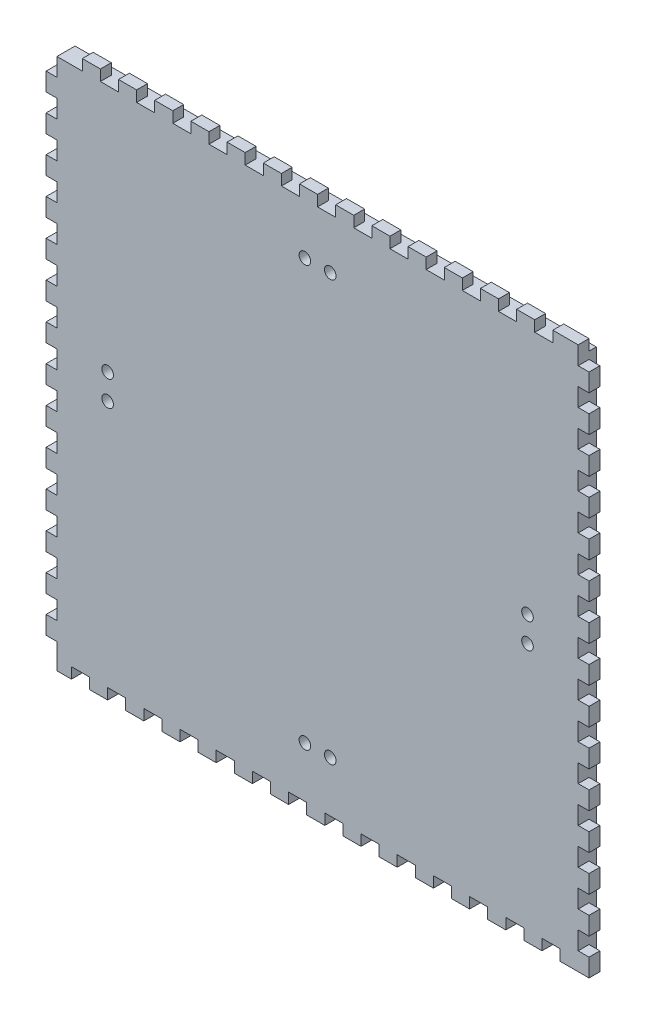
SolidWorks part; units mm, degrees
ref_plane "Front Plane" through (0, 0, 0) normal (0, 0, 1) x (1, 0, 0)
ref_plane "Top Plane" through (0, 0, 0) normal (0, 1, 0) x (1, 0, 0)
ref_plane "Right Plane" through (0, 0, 0) normal (1, 0, 0) x (0, 0, -1)
sketch "Sketch1" plane through (0, 0, 0) normal (0, 0, 1) x (1, 0, 0)
  line L1 (-75, 75) -> (75, 75)
  line L2 (-75, 75) -> (-75, -75)
  line L3 (-75, -75) -> (75, -75)
  line L4 (75, 75) -> (75, -75)
  line L5 (-75, 75) -> (75, -75) construction
  line L6 (-75, -75) -> (75, 75) construction
  point P0 (0, 0)
  dimension "D1" = 150
  dimension "D2" = 150
extrude "Boss-Extrude1" add sketch "Sketch1" along normal blind 5
sketch "Sketch2" plane through (0, 75, 0) normal (0, 1, 0) x (1, 0, 0)
  line L1 (-75, 0) -> (72, 0)
  line L2 (-75, 0) -> (-75, -2)
  line L3 (-75, -2) -> (72, -2)
  line L4 (72, 0) -> (72, -2)
  dimension "D1" = 2
  dimension "D2" = 3
extrude "Cut-Extrude1" cut sketch "Sketch2" against normal blind 3
sketch "Sketch3" plane through (0, 75, 0) normal (0, 1, 0) x (1, 0, 0)
  line L0 (75, -5) -> (-75, -5) construction
  line L1 (-60, -5) -> (-55, -5)
  line L2 (-60, -5) -> (-60, -2)
  line L3 (-60, -2) -> (-55, -2)
  line L4 (-55, -5) -> (-55, -2)
  line L5 (-75, -2) -> (72, -2) construction
  line L6 (-75, -5) -> (-75, -2) construction
  dimension "D1" = 5
  dimension "D2" = 15
extrude "Cut-Extrude2" cut sketch "Sketch3" against normal blind 3
pattern_linear "LPattern1" count 13 spacing 10 along (1, 0, 0) of "Cut-Extrude2"
sketch "Sketch4" plane through (0, 75, 0) normal (0, 1, 0) x (1, 0, 0)
  line L0 (-60, -5) -> (-75, -5) construction
  line L1 (-72, -5) -> (-65, -5)
  line L2 (-72, -5) -> (-72, -2)
  line L3 (-72, -2) -> (-65, -2)
  line L4 (-65, -5) -> (-65, -2)
  line L5 (-75, -2) -> (-60, -2) construction
  line L6 (-75, -5) -> (-75, -2) construction
  dimension "D1" = 7
  dimension "D2" = 3
extrude "Cut-Extrude3" cut sketch "Sketch4" against normal blind 3
sketch "Sketch5" plane through (75, 0, 0) normal (1, 0, 0) x (0, 0, -1)
  line L0 (-5, -75) -> (-5, 75) construction
  line L1 (0, 75) -> (-5, 75)
  line L2 (0, 75) -> (0, 70)
  line L3 (0, 70) -> (-5, 70)
  line L4 (-5, 75) -> (-5, 70)
  line L5 (0, 65) -> (0, 60)
  line L6 (0, 65) -> (-5, 65)
  line L7 (-5, 65) -> (-5, 60)
  line L8 (0, 60) -> (-5, 60)
  line L9 (0, 55) -> (0, 50)
  line L10 (0, 55) -> (-5, 55)
  line L11 (-5, 55) -> (-5, 50)
  line L12 (0, 50) -> (-5, 50)
  line L13 (0, 45) -> (0, 40)
  line L14 (0, 45) -> (-5, 45)
  line L15 (-5, 45) -> (-5, 40)
  line L16 (0, 40) -> (-5, 40)
  line L17 (0, 35) -> (0, 30)
  line L18 (0, 35) -> (-5, 35)
  line L19 (-5, 35) -> (-5, 30)
  line L20 (0, 30) -> (-5, 30)
  line L21 (0, 25) -> (0, 20)
  line L22 (0, 25) -> (-5, 25)
  line L23 (-5, 25) -> (-5, 20)
  line L24 (0, 20) -> (-5, 20)
  line L25 (0, 15) -> (0, 10)
  line L26 (0, 15) -> (-5, 15)
  line L27 (-5, 15) -> (-5, 10)
  line L28 (0, 10) -> (-5, 10)
  line L29 (0, 5) -> (0, 0)
  line L30 (0, 5) -> (-5, 5)
  line L31 (-5, 5) -> (-5, 0)
  line L32 (0, 0) -> (-5, 0)
  line L33 (0, -5) -> (0, -10)
  line L34 (0, -5) -> (-5, -5)
  line L35 (-5, -5) -> (-5, -10)
  line L36 (0, -10) -> (-5, -10)
  line L37 (0, -15) -> (0, -20)
  line L38 (0, -15) -> (-5, -15)
  line L39 (-5, -15) -> (-5, -20)
  line L40 (0, -20) -> (-5, -20)
  line L41 (0, -25) -> (0, -30)
  line L42 (0, -25) -> (-5, -25)
  line L43 (-5, -25) -> (-5, -30)
  line L44 (0, -30) -> (-5, -30)
  line L45 (0, -35) -> (0, -40)
  line L46 (0, -35) -> (-5, -35)
  line L47 (-5, -35) -> (-5, -40)
  line L48 (0, -40) -> (-5, -40)
  line L49 (0, -45) -> (0, -50)
  line L50 (0, -45) -> (-5, -45)
  line L51 (-5, -45) -> (-5, -50)
  line L52 (0, -50) -> (-5, -50)
  line L53 (0, -55) -> (0, -60)
  line L54 (0, -55) -> (-5, -55)
  line L55 (-5, -55) -> (-5, -60)
  line L56 (0, -60) -> (-5, -60)
  line L57 (0, -65) -> (0, -70)
  line L58 (0, -65) -> (-5, -65)
  line L59 (-5, -65) -> (-5, -70)
  line L60 (0, -70) -> (-5, -70)
  dimension "D1" = 5
  dimension "D2" = 15
extrude "Cut-Extrude4" cut sketch "Sketch5" against normal blind 3
sketch "Sketch6" plane through (75, 0, 0) normal (1, 0, 0) x (0, 0, -1)
  line L0 (-5, -75) -> (0, -75) construction
  line L1 (0, 70) -> (-2, 70)
  line L2 (0, 70) -> (0, -75)
  line L3 (0, -75) -> (-2, -75)
  line L4 (-2, 70) -> (-2, -75)
  dimension "D1" = 2
extrude "Cut-Extrude5" cut sketch "Sketch6" against normal blind 3
sketch "Sketch7" plane through (-75, 0, 0) normal (-1, 0, 0) x (0, 0, 1)
  line L0 (5, -75) -> (0, -75) construction
  line L1 (0, 72) -> (2, 72)
  line L2 (0, 72) -> (0, -75)
  line L3 (0, -75) -> (2, -75)
  line L4 (2, 72) -> (2, -75)
extrude "Cut-Extrude6" cut sketch "Sketch7" against normal blind 3
sketch "Sketch8" plane through (-75, 0, 0) normal (-1, 0, 0) x (0, 0, 1)
  line L0 (2, -75) -> (2, 75) construction
  line L1 (5, 75) -> (2, 75)
  line L2 (5, 75) -> (5, 67)
  line L3 (5, 67) -> (2, 67)
  line L4 (2, 75) -> (2, 67)
  dimension "D1" = 8
extrude "Cut-Extrude7" cut sketch "Sketch8" against normal blind 3
sketch "Sketch9" plane through (-75, 0, 0) normal (-1, 0, 0) x (0, 0, 1)
  line L0 (5, 67) -> (5, -75) construction
  line L1 (5, 62) -> (2, 62)
  line L2 (5, 62) -> (5, 57)
  line L3 (5, 57) -> (2, 57)
  line L4 (2, 62) -> (2, 57)
  line L5 (2, -75) -> (2, 67) construction
  line L6 (2, 67) -> (5, 67) construction
  dimension "D1" = 5
  dimension "D2" = 5
extrude "Cut-Extrude8" cut sketch "Sketch9" against normal blind 3
pattern_linear "LPattern2" count 13 spacing 10 along (0, -1, 0) of "Cut-Extrude8"
sketch "Sketch10" plane through (-75, 0, 0) normal (-1, 0, 0) x (0, 0, 1)
  line L0 (5, -63) -> (5, -75) construction
  line L1 (2, -75) -> (5, -75)
  line L2 (2, -75) -> (2, -68)
  line L3 (2, -68) -> (5, -68)
  line L4 (5, -75) -> (5, -68)
  dimension "D1" = 7
extrude "Cut-Extrude9" cut sketch "Sketch10" against normal blind 3
sketch "Sketch11" plane through (0, -75, 0) normal (0, -1, 0) x (1, 0, 0)
  line L1 (-72, 0) -> (72, 0)
  line L2 (-72, 0) -> (-72, 2)
  line L3 (-72, 2) -> (72, 2)
  line L4 (72, 0) -> (72, 2)
extrude "Cut-Extrude10" cut sketch "Sketch11" against normal blind 3
sketch "Sketch12" plane through (0, -75, 0) normal (0, -1, 0) x (1, 0, 0)
  line L0 (-72, 5) -> (75, 5) construction
  line L1 (67, 5) -> (62, 5)
  line L2 (67, 5) -> (67, 2)
  line L3 (67, 2) -> (62, 2)
  line L4 (62, 5) -> (62, 2)
  line L5 (-72, 2) -> (75, 2) construction
  line L6 (75, 5) -> (75, 2) construction
  dimension "D1" = 8
  dimension "D2" = 5
extrude "Cut-Extrude11" cut sketch "Sketch12" against normal blind 3
pattern_linear "LPattern3" count 14 spacing 10 along (-1, 0, 0) of "Cut-Extrude11"
sketch "Sketch13" plane through (0, 0, 0) normal (0, 0, -1) x (-1, 0, 0)
  line L3 (5, 72) -> (0, 72) construction
  line L4 (-72, 72) -> (72, 72) construction
  line L5 (-72, 0) -> (-72, -5) construction
  line L6 (-72, -72) -> (-72, 72) construction
  circle A0 centre (-3.5, 58) radius 1.6
  circle A1 centre (3.5, 58) radius 1.6
  circle A2 centre (-58, 3.5) radius 1.6
  circle A3 centre (-58, -3.5) radius 1.6
  dimension "D1" = 3.2
  dimension "D2" = 3.2
  dimension "D7" = 3.2
  dimension "D8" = 3.2
  dimension "D3" = 14
  dimension "D4" = 14
  dimension "D5" = 3.5
  dimension "D6" = 3.5
  dimension "D9" = 14
  dimension "D10" = 14
  dimension "D11" = 3.5
  dimension "D12" = 3.5
extrude "Cut-Extrude12" cut sketch "Sketch13" against normal blind 15
mirror "Mirror1" about plane through (0, 0, 0) normal (0, 1, 0) of "Cut-Extrude12"
mirror "Mirror2" about plane through (0, 0, 0) normal (1, 0, 0) of "Mirror1"
